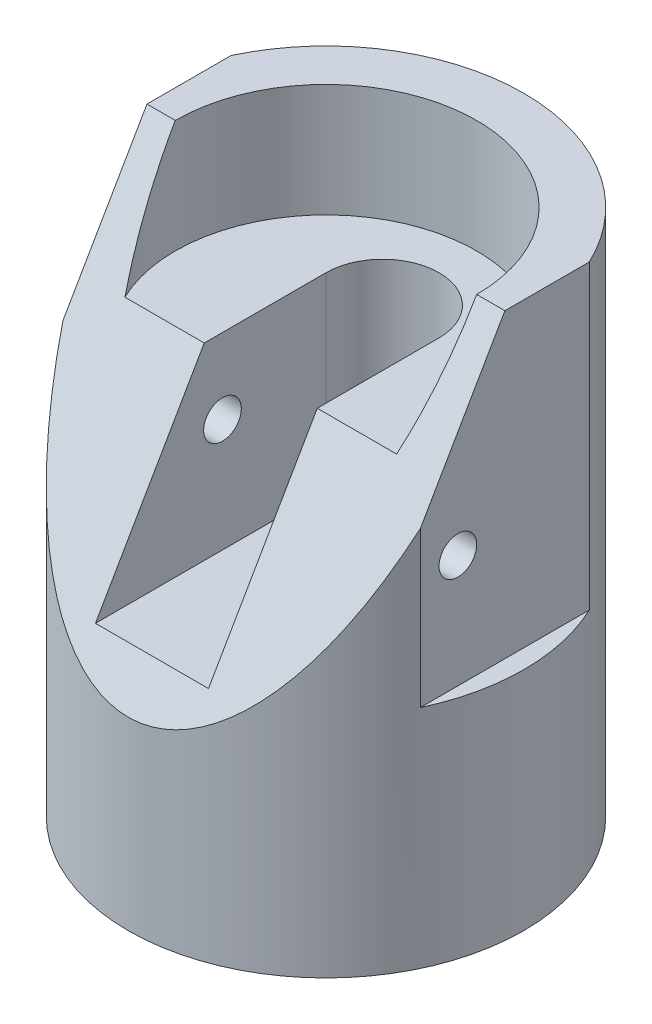
SolidWorks part; units mm, degrees
ref_plane "Alzado" through (0, 0, 0) normal (0, 0, 1) x (1, 0, 0)
ref_plane "Planta" through (0, 0, 0) normal (0, 1, 0) x (1, 0, 0)
ref_plane "Vista lateral" through (0, 0, 0) normal (1, 0, 0) x (0, 0, -1)
sketch "Croquis2" plane through (0, 0, 0) normal (0, 1, 0) x (1, 0, 0)
  line L1 (-33.3375, -33.3375) -> (33.3375, -33.3375)
  line L2 (-33.3375, -33.3375) -> (-33.3375, 33.3375)
  line L3 (-33.3375, 33.3375) -> (33.3375, 33.3375)
  line L4 (33.3375, -33.3375) -> (33.3375, 33.3375)
  line L5 (-33.3375, -33.3375) -> (33.3375, 33.3375) construction
  line L6 (-33.3375, 33.3375) -> (33.3375, -33.3375) construction
  point P0 (0, 0)
  dimension "D1" = 66.675
extrude "Saliente-Extruir2" add sketch "Croquis2" along normal blind 88.9 contours L2 L1 L4 L3
sketch "Croquis4" plane through (-33.3375, 0, 0) normal (-1, 0, 0) x (0, 0, 1)
  line L0 (0, 88.9) -> (0, 0) construction
  line L1 (33.3375, 88.9) -> (-33.3375, 88.9) construction
  line L2 (33.3375, 31.1578) -> (0, 88.9)
  line L3 (0, 88.9) -> (33.3375, 88.9)
  line L4 (33.3375, 88.9) -> (33.3375, 31.1578)
  line L5 (33.3375, 88.9) -> (33.3375, 0) construction
  dimension "D1" = 30
extrude "Cortar-Extruir1" cut sketch "Croquis4" against normal through all
sketch "Croquis5" plane through (0, 0, 0) normal (0, -1, 0) x (1, 0, 0)
  circle A0 centre (0, 0) radius 33.3375
extrude "Cortar-Extruir2" cut sketch "Croquis5" against normal blind 88.9 flip side to cut
sketch "Croquis6" plane through (0, 88.9, 0) normal (0, 1, 0) x (1, 0, 0)
  circle A0 centre (0, 0) radius 25.4
  dimension "D1" = 50.8
extrude "Cortar-Extruir4" cut sketch "Croquis6" against normal blind 19.05
sketch "Croquis7" plane through (0, 69.85, 0) normal (0, 1, 0) x (1, 0, 0)
  line L0 (0, 0) -> (0, 9.525) construction
  line L1 (-9.525, 9.525) -> (-9.525, -31.9478)
  line L2 (-9.525, -31.9478) -> (9.525, -31.9478)
  line L3 (9.525, 9.525) -> (9.525, -31.9478)
  arc A0 (9.525, 9.525) -> (-9.525, 9.525) centre (0, 9.525) ccw
  arc A1 (-33.3375, 0) -> (33.3375, 0) centre (0, 0) ccw construction
  dimension "D2" = 19.05
  dimension "D1" = 9.525
extrude "Cortar-Extruir5" cut sketch "Croquis7" against normal blind 31.75
sketch "Croquis8" plane through (0, 88.9, 0) normal (0, 1, 0) x (1, 0, 0)
  line L0 (-30.1752, 14.172) -> (-30.1752, -14.172)
  line L1 (30.1498, 14.226) -> (30.1498, -14.226)
  arc A0 (-30.1752, 14.172) -> (-30.1752, -14.172) centre (0, 0) ccw
  arc A1 (33.3375, 0) -> (-33.3375, 0) centre (0, 0) ccw construction
  arc A2 (30.1498, -14.226) -> (30.1498, 14.226) centre (0, 0) ccw
  arc A3 (-33.3375, 0) -> (33.3375, 0) centre (0, 0) ccw construction
  dimension "D1" = 60.325
  dimension "D2" = 30.1752
extrude "Cortar-Extruir6" cut sketch "Croquis8" against normal blind 50.8
sketch "Croquis9" plane through (-30.1752, 0, 0) normal (-1, 0, 0) x (0, 0, 1)
  line L0 (0, -5.5619) -> (0, 90.8944) construction
  line L1 (7.9248, 68.1677) -> (7.9248, 41.3449) construction
  line L2 (-9.6456, 57.15) -> (12.6847, 57.15) construction
  line L3 (0, 88.9) -> (-14.172, 88.9) construction
  circle A0 centre (7.9248, 57.15) radius 3.175
  dimension "D3" = 6.35
  dimension "D1" = 31.75
  dimension "D2" = 7.9248
extrude "Cortar-Extruir7" cut sketch "Croquis9" against normal blind 60.325
